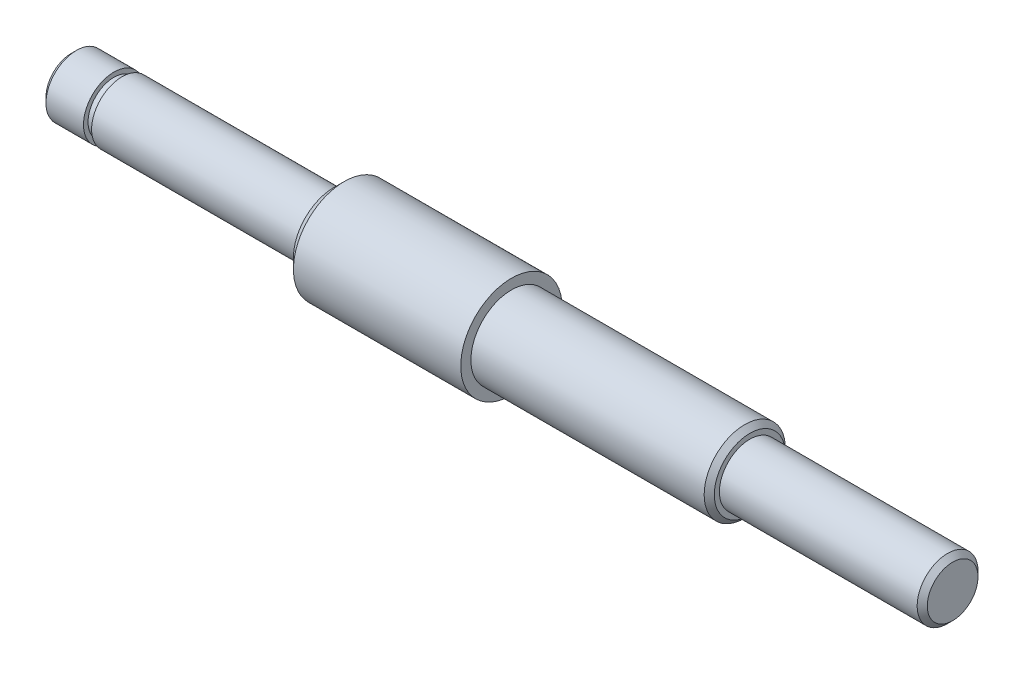
SolidWorks part; units mm, degrees
ref_plane "Alzado" through (0, 0, 0) normal (1, 0, 0) x (0, 1, 0)
ref_plane "Planta" through (0, 0, 0) normal (0, 0, 1) x (0, 1, 0)
ref_plane "Vista lateral" through (0, 0, 0) normal (0, 1, 0) x (-1, 0, 0)
sketch "Croquis1" plane through (0, 0, 0) normal (0, 1, 0) x (-1, 0, 0)
  line L0 (-43.45, 0) -> (-43.45, 3)
  line L1 (-43.45, 3) -> (-23.45, 3)
  line L2 (-23.45, 3) -> (-23.45, 4)
  line L3 (-23.45, 4) -> (0.05, 4)
  line L6 (43.45, 3) -> (43.45, 0)
  line L7 (-43.45, 0) -> (43.45, 0) construction
  line L9 (38.45, 3) -> (38.45, 2.55)
  line L10 (38.45, 2.55) -> (39.25, 2.55)
  line L11 (39.25, 2.55) -> (39.25, 3)
  line L12 (39.25, 3) -> (43.45, 3)
  line L14 (0.05, 4) -> (0.05, 5)
  line L15 (0.05, 5) -> (17.55, 5)
  line L16 (17.55, 5) -> (17.55, 3)
  line L17 (17.55, 3) -> (38.45, 3)
  line L18 (-43.45, 0) -> (43.45, 0)
  point P6 (43.45, 1.5)
  dimension "D2" = 6
  dimension "D4" = 8
  dimension "D8" = 0.8
  dimension "D6" = 0.45
  dimension "D1" = 20
  dimension "D9" = 20.9
  dimension "D12" = 10
  dimension "D10" = 43.5
  dimension "D5" = 5
  dimension "D3" = 17.5
revolve "Revolución1" add sketch "Croquis1" angle 360 about L7
chamfer "Chaflán1" distance 0.5 angle 45 3 edges at (-43.45, 0, -3) (43.45, 0, -3) (23.45, 0, -4)
chamfer "Chaflán2" distance 1 angle 45 1 edges at (-17.55, 0, -5)
equation "\"ancho_circlip\"=0.8"
equation "\"D8@Croquis1\"=\"ancho_circlip\""
equation "\"ranura_circlip\"=0.45"
equation "\"D6@Croquis1\"=\"ranura_circlip\""
